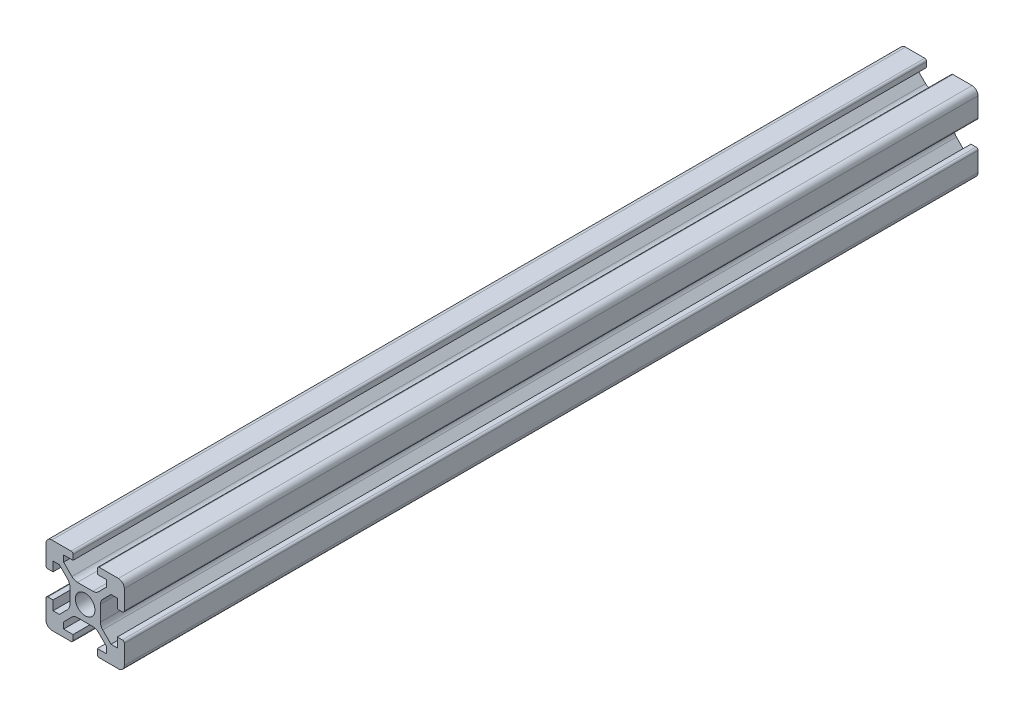
SolidWorks part; units mm, degrees
ref_plane "前视基准面" through (0, 0, 0) normal (0, 0, 1) x (1, 0, 0)
ref_plane "上视基准面" through (0, 0, 0) normal (0, 1, 0) x (1, 0, 0)
ref_plane "右视基准面" through (0, 0, 0) normal (1, 0, 0) x (0, 0, -1)
sketch "草图1" plane through (0, 0, 0) normal (0, 0, 1) x (1, 0, 0)
  line L0 (-19.2539, 0) -> (18.8323, 0) construction
  line L1 (0, 18.4429) -> (0, -19.8143) construction
  line L2 (3.9, 0) -> (3.9, 1.9716)
  line L3 (-8.5, 10) -> (-3.6, 10)
  line L4 (-10, 8.5) -> (-10, 3.6)
  line L5 (-8.5, -10) -> (-3.6, -10)
  line L6 (10, 8.5) -> (10, 3.6)
  line L7 (-10, 10) -> (10, -10) construction
  line L8 (-10, -10) -> (10, 10) construction
  line L9 (4.4858, 3.3858) -> (6.6, 5.5)
  line L10 (6.6, 5.5) -> (8.2, 5.5)
  line L11 (8.2, 5.5) -> (8.2, 3.1)
  line L12 (8.2, 3.1) -> (9.5, 3.1)
  line L17 (8.2, -3.1) -> (9.5, -3.1)
  line L18 (8.2, -5.5) -> (8.2, -3.1)
  line L19 (6.6, -5.5) -> (8.2, -5.5)
  line L20 (4.4858, -3.3858) -> (6.6, -5.5)
  line L21 (3.9, 0) -> (3.9, -1.9716)
  line L22 (10, -3.6) -> (10, -8.5)
  line L23 (-3.1, 8.2) -> (-3.1, 9.5)
  line L24 (-5.5, 8.2) -> (-3.1, 8.2)
  line L25 (-5.5, 6.6) -> (-5.5, 8.2)
  line L26 (-3.3858, 4.4858) -> (-5.5, 6.6)
  line L27 (0, 3.9) -> (-1.9716, 3.9)
  line L28 (0, 3.9) -> (1.9716, 3.9)
  line L29 (3.3858, 4.4858) -> (5.5, 6.6)
  line L30 (5.5, 6.6) -> (5.5, 8.2)
  line L31 (5.5, 8.2) -> (3.1, 8.2)
  line L32 (3.1, 8.2) -> (3.1, 9.5)
  line L33 (3.6, 10) -> (8.5, 10)
  line L34 (-8.2, -3.1) -> (-9.5, -3.1)
  line L35 (-8.2, -5.5) -> (-8.2, -3.1)
  line L36 (-6.6, -5.5) -> (-8.2, -5.5)
  line L37 (-4.4858, -3.3858) -> (-6.6, -5.5)
  line L38 (-3.9, 0) -> (-3.9, -1.9716)
  line L39 (-3.9, 0) -> (-3.9, 1.9716)
  line L40 (-4.4858, 3.3858) -> (-6.6, 5.5)
  line L41 (-6.6, 5.5) -> (-8.2, 5.5)
  line L42 (-8.2, 5.5) -> (-8.2, 3.1)
  line L43 (-8.2, 3.1) -> (-9.5, 3.1)
  line L44 (3.1, -8.2) -> (3.1, -9.5)
  line L45 (5.5, -8.2) -> (3.1, -8.2)
  line L46 (5.5, -6.6) -> (5.5, -8.2)
  line L47 (3.3858, -4.4858) -> (5.5, -6.6)
  line L48 (0, -3.9) -> (1.9716, -3.9)
  line L49 (0, -3.9) -> (-1.9716, -3.9)
  line L50 (-3.3858, -4.4858) -> (-5.5, -6.6)
  line L51 (-5.5, -6.6) -> (-5.5, -8.2)
  line L52 (-5.5, -8.2) -> (-3.1, -8.2)
  line L53 (-3.1, -8.2) -> (-3.1, -9.5)
  line L54 (3.6, -10) -> (8.5, -10)
  line L55 (-10, -3.6) -> (-10, -8.5)
  circle A0 centre (0, 0) radius 2.5
  arc A1 (3.9, 1.9716) -> (4.4858, 3.3858) centre (5.9, 1.9716) cw
  arc A2 (4.4858, -3.3858) -> (3.9, -1.9716) centre (5.9, -1.9716) cw
  arc A5 (10, 8.5) -> (8.5, 10) centre (8.5, 8.5) ccw
  arc A6 (-10, 8.5) -> (-8.5, 10) centre (-8.5, 8.5) cw
  arc A7 (-8.5, -10) -> (-10, -8.5) centre (-8.5, -8.5) cw
  arc A8 (10, -8.5) -> (8.5, -10) centre (8.5, -8.5) cw
  arc A9 (9.5, 3.1) -> (10, 3.6) centre (9.5, 3.6) ccw
  arc A10 (10, -3.6) -> (9.5, -3.1) centre (9.5, -3.6) ccw
  arc A11 (-3.6, 10) -> (-3.1, 9.5) centre (-3.6, 9.5) cw
  arc A12 (-3.3858, 4.4858) -> (-1.9716, 3.9) centre (-1.9716, 5.9) ccw
  arc A13 (1.9716, 3.9) -> (3.3858, 4.4858) centre (1.9716, 5.9) ccw
  arc A14 (3.1, 9.5) -> (3.6, 10) centre (3.6, 9.5) cw
  arc A15 (-10, -3.6) -> (-9.5, -3.1) centre (-9.5, -3.6) cw
  arc A16 (-4.4858, -3.3858) -> (-3.9, -1.9716) centre (-5.9, -1.9716) ccw
  arc A17 (-3.9, 1.9716) -> (-4.4858, 3.3858) centre (-5.9, 1.9716) ccw
  arc A18 (-9.5, 3.1) -> (-10, 3.6) centre (-9.5, 3.6) cw
  arc A19 (3.6, -10) -> (3.1, -9.5) centre (3.6, -9.5) cw
  arc A20 (3.3858, -4.4858) -> (1.9716, -3.9) centre (1.9716, -5.9) ccw
  arc A21 (-1.9716, -3.9) -> (-3.3858, -4.4858) centre (-1.9716, -5.9) ccw
  arc A22 (-3.1, -9.5) -> (-3.6, -10) centre (-3.6, -9.5) cw
  point P34 (3.9, 2.8)
  point P37 (3.9, -2.8)
  point P42 (10, 3.1)
  point P53 (10, -3.1)
  dimension "D1" = 5
  dimension "D10" = 2
  dimension "D13" = 1.5
  dimension "D8" = 0.5
  dimension "D3" = 6.1
  dimension "D4" = 11
  dimension "D5" = 6.2
  dimension "D6" = 1.8
  dimension "D7" = 3.4
  dimension "D16" = 20
extrude "凸台-拉伸1" add sketch "草图1" along normal blind 218
